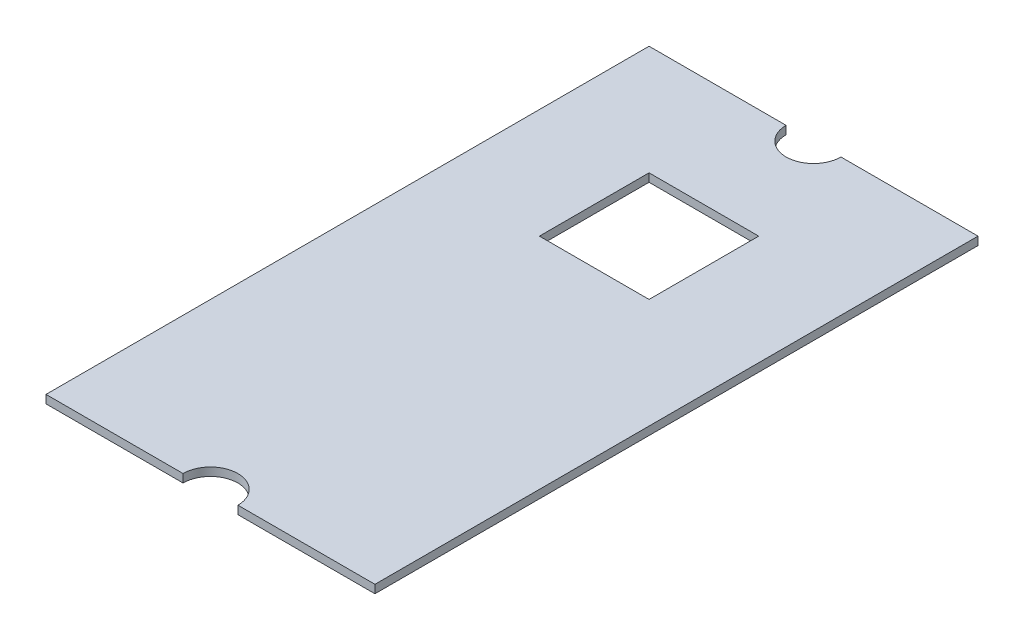
SolidWorks part; units mm, degrees
ref_plane "Front Plane" through (0, 0, 0) normal (0, 0, 1) x (1, 0, 0)
ref_plane "Top Plane" through (0, 0, 0) normal (0, 1, 0) x (1, 0, 0)
ref_plane "Right Plane" through (0, 0, 0) normal (1, 0, 0) x (0, 0, -1)
sketch "Sketch1" plane through (0, 0, 0) normal (0, 0, 1) x (1, 0, 0)
  line L1 (0, 0) -> (120, 0)
  line L2 (0, 0) -> (0, 3)
  line L3 (0, 3) -> (120, 3)
  line L4 (120, 0) -> (120, 3)
  dimension "D1" = 120
  dimension "D2" = 3
extrude "Boss-Extrude1" add sketch "Sketch1" along normal blind 220
ref_plane "Plane1" through (0, 3, 0) normal (0, 1, 0) x (1, 0, 0)
sketch "Sketch2" plane through (0, 3, 0) normal (0, 1, 0) x (1, 0, 0)
  line L0 (120, -220) -> (0, -220) construction
  line L1 (120, -220) -> (120, 0) construction
  line L2 (0, -220) -> (0, 0) construction
  line L3 (120, 0) -> (0, 0) construction
  circle A0 centre (60, -220) radius 10
  circle A1 centre (60, 0) radius 10
  point P12 (0, 0)
  point P13 (60, -10)
  dimension "D1" = 20
  dimension "D2" = 0
  dimension "D3" = 60
  dimension "D4" = 60
  dimension "D5" = 60
  dimension "D6" = 20
  dimension "D7" = 0
  dimension "D8" = 60
extrude "Cut-Extrude1" cut sketch "Sketch2" against normal blind 10
sketch "Sketch4" plane through (0, 3, 0) normal (0, 1, 0) x (1, 0, 0)
  line L0 (60, -220) -> (60, 0) construction
  line L1 (120, 0) -> (70, 0) construction
  line L2 (40, -40) -> (80, -40)
  line L3 (40, -40) -> (40, -80)
  line L4 (40, -80) -> (80, -80)
  line L5 (80, -40) -> (80, -80)
  line L6 (40, -40) -> (80, -80) construction
  line L7 (40, -80) -> (80, -40) construction
  point P4 (60, -60)
  dimension "D1" = 40
  dimension "D2" = 40
  dimension "40" = 40
extrude "Cut-Extrude2" cut sketch "Sketch4" against normal blind 10
